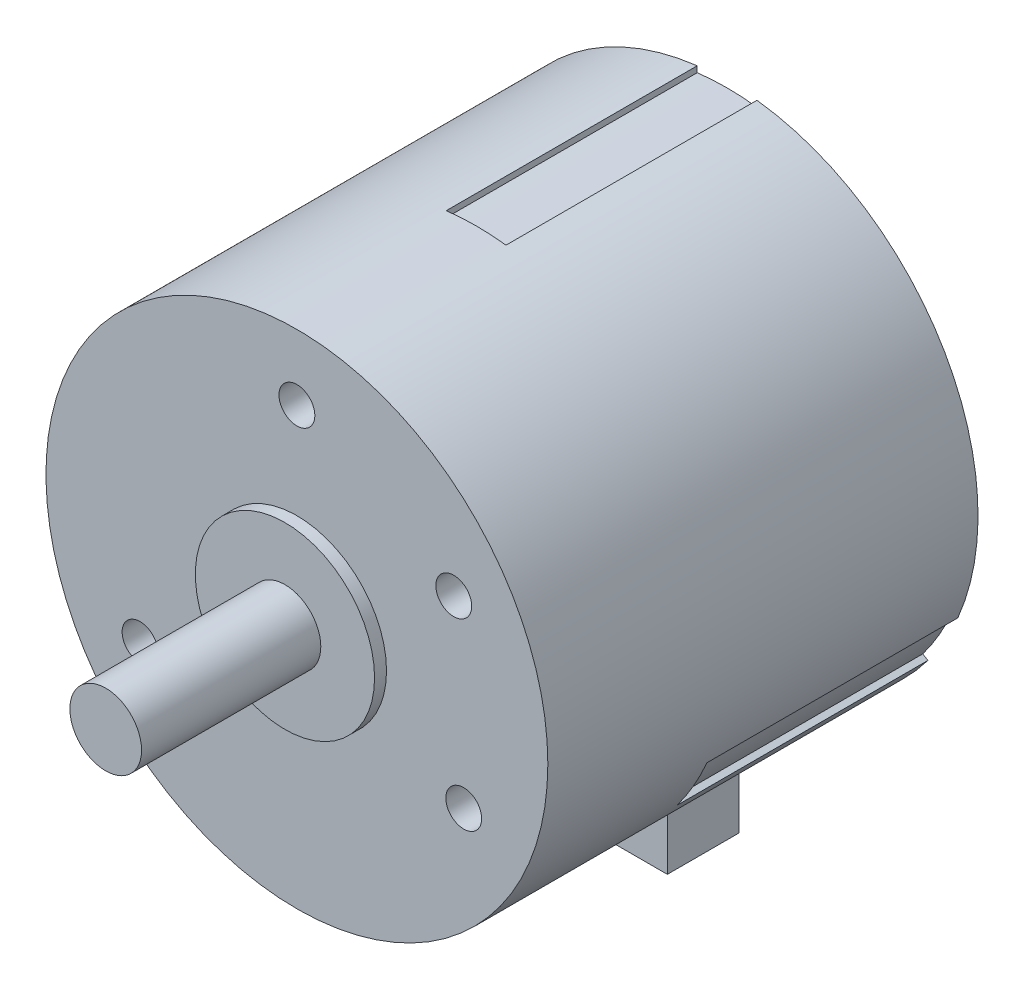
SolidWorks part; units mm, degrees
ref_plane "前视基准面" through (0, 0, 0) normal (0, 0, 1) x (1, 0, 0)
ref_plane "上视基准面" through (0, 0, 0) normal (0, 1, 0) x (1, 0, 0)
ref_plane "右视基准面" through (0, 0, 0) normal (1, 0, 0) x (0, 0, -1)
other "Configuration Table"
sketch "草图1" plane through (0, 0, 0) normal (0, 0, 1) x (1, 0, 0)
  circle A0 centre (0, 0) radius 21
extrude "凸台-拉伸1" add sketch "草图1" along normal blind 15
sketch "草图2" plane through (0, 0, 0) normal (0, 0, -1) x (-1, 0, 0)
  line L0 (2.5, 20.8507) -> (2.5, 20.347)
  line L1 (0, 8.25) -> (0, -8.25) construction
  line L2 (-2.5, 20.8507) -> (-2.5, 20.347)
  line L3 (19.3072, -8.2603) -> (18.871, -8.0084)
  line L4 (16.8072, -12.5904) -> (16.371, -12.3386)
  line L5 (-16.8072, -12.5904) -> (-16.371, -12.3386)
  line L6 (-19.3072, -8.2603) -> (-18.871, -8.0084)
  line L7 (15, -13.9732) -> (15, -14.6969)
  line L8 (-15, -13.9732) -> (-15, -14.6969)
  arc A0 (-2.5, 20.8507) -> (-19.3072, -8.2603) centre (0, 0) ccw
  circle A1 centre (0, 0) radius 21 construction
  arc A2 (-18.871, -8.0084) -> (-16.371, -12.3386) centre (0, 0) ccw
  arc A3 (19.3072, -8.2603) -> (2.5, 20.8507) centre (0, 0) ccw
  arc A4 (-16.8072, -12.5904) -> (-15, -14.6969) centre (0, 0) ccw
  arc A5 (15, -14.6969) -> (16.8072, -12.5904) centre (0, 0) ccw
  arc A6 (-15, -13.9732) -> (15, -13.9732) centre (0, 0) ccw
  arc A7 (16.371, -12.3386) -> (18.871, -8.0084) centre (0, 0) ccw
  arc A8 (2.5, 20.347) -> (-2.5, 20.347) centre (0, 0) ccw
  point P22 (0, 0)
  dimension "D1" = 5
  dimension "D2" = 3
  dimension "D3" = 30
extrude "凸台-拉伸2" add sketch "草图2" along normal blind 6
sketch "草图4" plane through (0, 0, -6) normal (0, 0, -1) x (-1, 0, 0)
  line L0 (10, -17.8955) -> (10, -24)
  line L1 (0, 11.55) -> (0, -11.55) construction
  line L2 (-10, -17.8955) -> (-10, -24)
  line L3 (-10, -24) -> (10, -24)
  line L8 (2.5, 20.8507) -> (2.5, 20.347)
  line L9 (-2.5, 20.347) -> (-2.5, 20.8507)
  line L10 (-19.3072, -8.2603) -> (-18.871, -8.0084)
  line L11 (-16.371, -12.3386) -> (-16.8072, -12.5904)
  line L12 (-15, -14.6969) -> (-15, -13.9732)
  line L13 (15, -13.9732) -> (15, -14.6969)
  line L14 (16.8072, -12.5904) -> (16.371, -12.3386)
  line L15 (18.871, -8.0084) -> (19.3072, -8.2603)
  line L16 (2.5, 20.8507) -> (2.5, 20.347)
  line L17 (-2.5, 20.347) -> (-2.5, 20.8507)
  line L18 (-19.3072, -8.2603) -> (-18.871, -8.0084)
  line L19 (-16.371, -12.3386) -> (-16.8072, -12.5904)
  line L20 (-15, -14.6969) -> (-15, -13.9732)
  line L21 (15, -13.9732) -> (15, -14.6969)
  line L22 (16.8072, -12.5904) -> (16.371, -12.3386)
  line L23 (18.871, -8.0084) -> (19.3072, -8.2603)
  arc A0 (10, -17.8955) -> (15, -13.9732) centre (0, 0) ccw
  arc A8 (19.3072, -8.2603) -> (2.5, 20.8507) centre (0, 0) ccw
  arc A9 (2.5, 20.347) -> (-2.5, 20.347) centre (0, 0) ccw
  arc A10 (-2.5, 20.8507) -> (-19.3072, -8.2603) centre (0, 0) ccw
  arc A11 (-18.871, -8.0084) -> (-16.371, -12.3386) centre (0, 0) ccw
  arc A12 (-16.8072, -12.5904) -> (-15, -14.6969) centre (0, 0) ccw
  arc A13 (-15, -13.9732) -> (15, -13.9732) centre (0, 0) ccw
  arc A14 (15, -14.6969) -> (16.8072, -12.5904) centre (0, 0) ccw
  arc A15 (16.371, -12.3386) -> (18.871, -8.0084) centre (0, 0) ccw
  arc A16 (19.3072, -8.2603) -> (2.5, 20.8507) centre (0, 0) ccw
  arc A17 (2.5, 20.347) -> (-2.5, 20.347) centre (0, 0) ccw
  arc A18 (-2.5, 20.8507) -> (-19.3072, -8.2603) centre (0, 0) ccw
  arc A19 (-18.871, -8.0084) -> (-16.371, -12.3386) centre (0, 0) ccw
  arc A20 (-16.8072, -12.5904) -> (-15, -14.6969) centre (0, 0) ccw
  arc A21 (-15, -13.9732) -> (-10, -17.8955) centre (0, 0) ccw
  arc A22 (15, -14.6969) -> (16.8072, -12.5904) centre (0, 0) ccw
  arc A23 (16.371, -12.3386) -> (18.871, -8.0084) centre (0, 0) ccw
  dimension "D2" = 20
  dimension "D3" = 24
  dimension "D1" = 0
extrude "凸台-拉伸3" add sketch "草图4" along normal blind 6
sketch "草图5" plane through (0, 0, -12) normal (0, 0, -1) x (-1, 0, 0)
  line L8 (18.871, -8.0084) -> (19.3072, -8.2603)
  line L9 (2.5, 20.8507) -> (2.5, 20.347)
  line L10 (-2.5, 20.347) -> (-2.5, 20.8507)
  line L11 (-19.3072, -8.2603) -> (-18.871, -8.0084)
  line L12 (-16.371, -12.3386) -> (-16.8072, -12.5904)
  line L13 (-15, -14.6969) -> (-15, -13.9732)
  line L14 (15, -13.9732) -> (15, -14.6969)
  line L15 (16.8072, -12.5904) -> (16.371, -12.3386)
  line L16 (18.871, -8.0084) -> (19.3072, -8.2603)
  line L17 (2.5, 20.8507) -> (2.5, 20.347)
  line L18 (-2.5, 20.347) -> (-2.5, 20.8507)
  line L19 (-19.3072, -8.2603) -> (-18.871, -8.0084)
  line L20 (-16.371, -12.3386) -> (-16.8072, -12.5904)
  line L23 (16.8072, -12.5904) -> (16.371, -12.3386)
  arc A0 (-15, -14.6969) -> (15, -14.6969) centre (0, 0) ccw
  arc A1 (-15, -14.6969) -> (15, -14.6969) centre (0, 0) ccw construction
  arc A8 (19.3072, -8.2603) -> (2.5, 20.8507) centre (0, 0) ccw
  arc A9 (2.5, 20.347) -> (-2.5, 20.347) centre (0, 0) ccw
  arc A10 (-2.5, 20.8507) -> (-19.3072, -8.2603) centre (0, 0) ccw
  arc A11 (-18.871, -8.0084) -> (-16.371, -12.3386) centre (0, 0) ccw
  arc A12 (-16.8072, -12.5904) -> (-15, -14.6969) centre (0, 0) ccw
  arc A13 (-15, -13.9732) -> (15, -13.9732) centre (0, 0) ccw
  arc A14 (15, -14.6969) -> (16.8072, -12.5904) centre (0, 0) ccw
  arc A15 (16.371, -12.3386) -> (18.871, -8.0084) centre (0, 0) ccw
  arc A16 (19.3072, -8.2603) -> (2.5, 20.8507) centre (0, 0) ccw
  arc A17 (2.5, 20.347) -> (-2.5, 20.347) centre (0, 0) ccw
  arc A18 (-2.5, 20.8507) -> (-19.3072, -8.2603) centre (0, 0) ccw
  arc A19 (-18.871, -8.0084) -> (-16.371, -12.3386) centre (0, 0) ccw
  arc A20 (-16.8072, -12.5904) -> (-15, -14.6969) centre (0, 0) ccw
  arc A22 (15, -14.6969) -> (16.8072, -12.5904) centre (0, 0) ccw
  arc A23 (16.371, -12.3386) -> (18.871, -8.0084) centre (0, 0) ccw
  dimension "D1" = 0
extrude "凸台-拉伸4" add sketch "草图5" along normal blind 9
sketch "草图6" plane through (0, 0, 15) normal (0, 0, 1) x (1, 0, 0)
  circle A0 centre (0, 0) radius 7.5
  dimension "D1" = 15
extrude "凸台-拉伸5" add sketch "草图6" along normal blind 1
sketch "草图7" plane through (0, 0, 16) normal (0, 0, 1) x (1, 0, 0)
  circle A0 centre (0, 0) radius 3
extrude "凸台-拉伸6" add sketch "草图7" along normal blind 15
sketch "草图8" plane through (0, 0, 15) normal (0, 0, 1) x (1, 0, 0)
  circle A0 centre (0, 0) radius 15.5 construction
  circle A1 centre (0, 15.5) radius 1.5
  circle A2 centre (13.1271, 8.2419) radius 1.5
  circle A3 centre (13.9603, -6.7349) radius 1.5
  circle A4 centre (-13.1271, -8.2419) radius 1.5
  point P14 (0, 0)
  dimension "D1" = 15
  dimension "D2" = 15
  dimension "D3" = 2
extrude "切除-拉伸1" cut sketch "草图8" against normal blind 3
